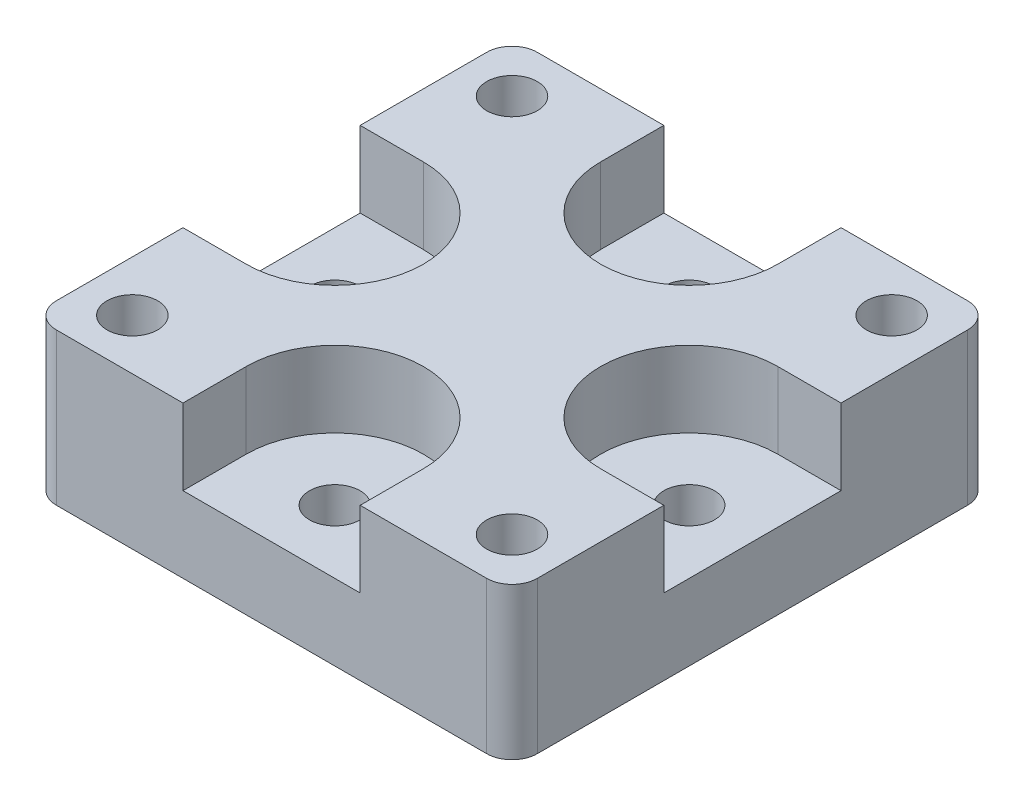
SolidWorks part; units mm, degrees
ref_plane "Спереди" through (0, 0, 0) normal (0, 0, 1) x (1, 0, 0)
ref_plane "Сверху" through (0, 0, 0) normal (0, 1, 0) x (1, 0, 0)
ref_plane "Справа" through (0, 0, 0) normal (1, 0, 0) x (0, 0, -1)
sketch "Эскиз1" plane through (0, 0, 0) normal (0, 1, 0) x (1, 0, 0)
  line L0 (0, 0) -> (19, 0)
  line L1 (19, 0) -> (19, 19)
  line L2 (0, 0) -> (0, 19)
  line L3 (0, 19) -> (19, 19)
  line L5 (2, 2) -> (17, 2) construction
  line L6 (2, 2) -> (2, 17) construction
  line L7 (2, 17) -> (17, 17) construction
  line L8 (17, 2) -> (17, 17) construction
  circle A0 centre (2, 17) radius 1
  circle A1 centre (17, 17) radius 1
  circle A2 centre (17, 2) radius 1
  circle A3 centre (2, 2) radius 1
  dimension "D1" = 19
  dimension "D2" = 2
  dimension "D3" = 15
  dimension "D4" = 15
  dimension "D5" = 2
  dimension "D6" = 19
extrude "Бобышка-Вытянуть1" add sketch "Эскиз1" along normal blind 6
fillet "Скругление1" radius 1 4 edges at (19, 3, 0) (0, 3, 0) (0, 3, -19) (19, 3, -19)
sketch "Эскиз2" plane through (0, 6, 0) normal (0, 1, 0) x (1, 0, 0)
  line L0 (18, 19) -> (1, 19) construction
  line L1 (19, 1) -> (19, 18) construction
  circle A0 centre (9.5, 9.5) radius 7 construction
  circle A1 centre (9.5, 9.5) radius 8 construction
  circle A2 centre (9.5, 16.5) radius 1
  circle A3 centre (16.5, 9.5) radius 1
  circle A4 centre (9.5, 2.5) radius 1
  circle A5 centre (2.5, 9.5) radius 1
  point P4 (9.5, 19)
  point P8 (19, 9.5)
  dimension "D1" = 14
  dimension "D2" = 16
extrude "Вырез-Вытянуть1" cut sketch "Эскиз2" against normal through all
sketch "Эскиз3" plane through (0, 6, 0) normal (0, 1, 0) x (1, 0, 0)
  line L0 (6, 16.5) -> (6, 21.9359)
  line L1 (6, 21.9359) -> (13, 21.9359)
  line L2 (13, 21.9359) -> (13, 16.5)
  line L4 (13, 2.5) -> (13, -5.1029)
  line L5 (13, -5.1029) -> (6, -4.7992)
  line L6 (6, -4.7992) -> (6, 2.5)
  line L7 (2.5, 6) -> (-3.6989, 6)
  line L8 (-3.6989, 6) -> (-3.6989, 13)
  line L9 (-3.6989, 13) -> (2.5, 13)
  line L10 (22.8369, 13) -> (22.8369, 6)
  line L11 (22.8369, 6) -> (16.5, 6)
  line L12 (16.5, 13) -> (22.8369, 13)
  arc A0 (6, 16.5) -> (13, 16.5) centre (9.5, 16.5) ccw
  arc A1 (16.5, 13) -> (16.5, 6) centre (16.5, 9.5) ccw
  arc A2 (13, 2.5) -> (6, 2.5) centre (9.5, 2.5) ccw
  arc A3 (2.5, 6) -> (2.5, 13) centre (2.5, 9.5) ccw
extrude "Вырез-Вытянуть2" cut sketch "Эскиз3" against normal blind 3
